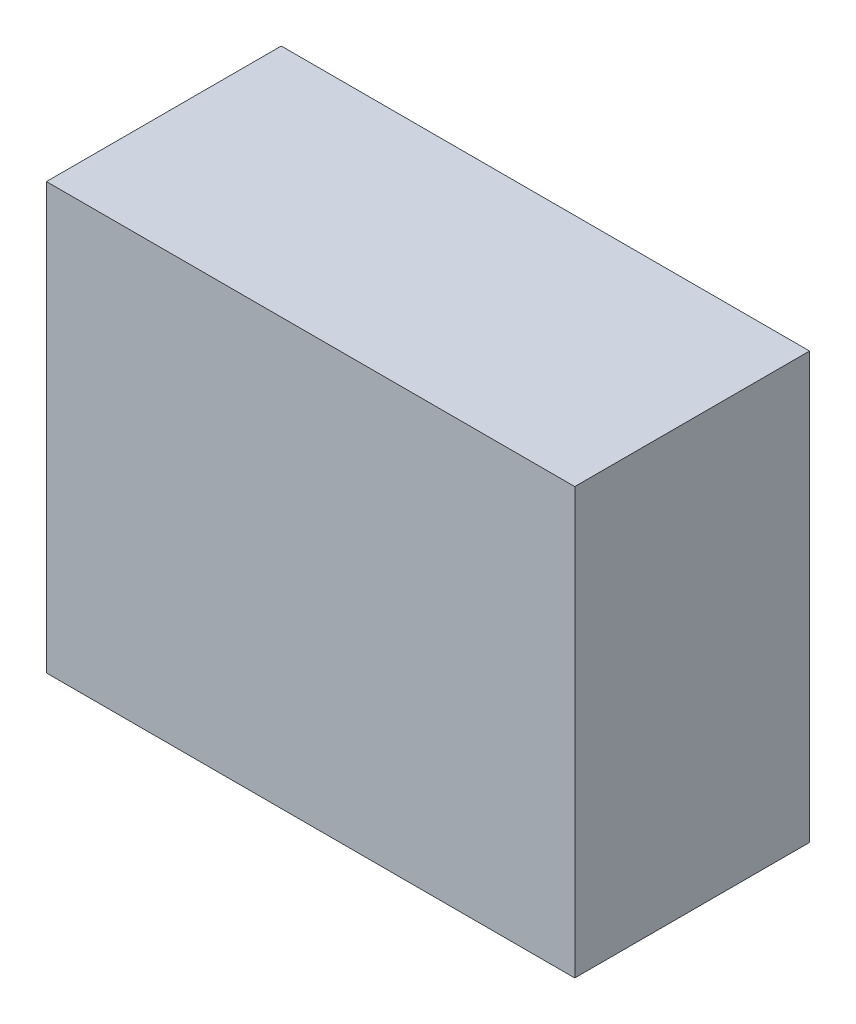
SolidWorks part; units mm, degrees
ref_plane "Front Plane" through (0, 0, 0) normal (0, 0, 1) x (1, 0, 0)
ref_plane "Top Plane" through (0, 0, 0) normal (0, 1, 0) x (1, 0, 0)
ref_plane "Right Plane" through (0, 0, 0) normal (1, 0, 0) x (0, 0, -1)
sketch "Sketch1" plane through (0, 0, 0) normal (0, 0, 1) x (1, 0, 0)
  line L1 (-405.9713, -309.7305) -> (-863.1713, -309.7305)
  line L2 (-405.9713, -309.7305) -> (-405.9713, 58.5695)
  line L3 (-405.9713, 58.5695) -> (-863.1713, 58.5695)
  line L4 (-863.1713, -309.7305) -> (-863.1713, 58.5695)
  point P4 (-634.5713, 58.5695)
  dimension "D1" = 457.2
  dimension "D2" = 368.3
extrude "Boss-Extrude1" add sketch "Sketch1" along normal blind 203.2
